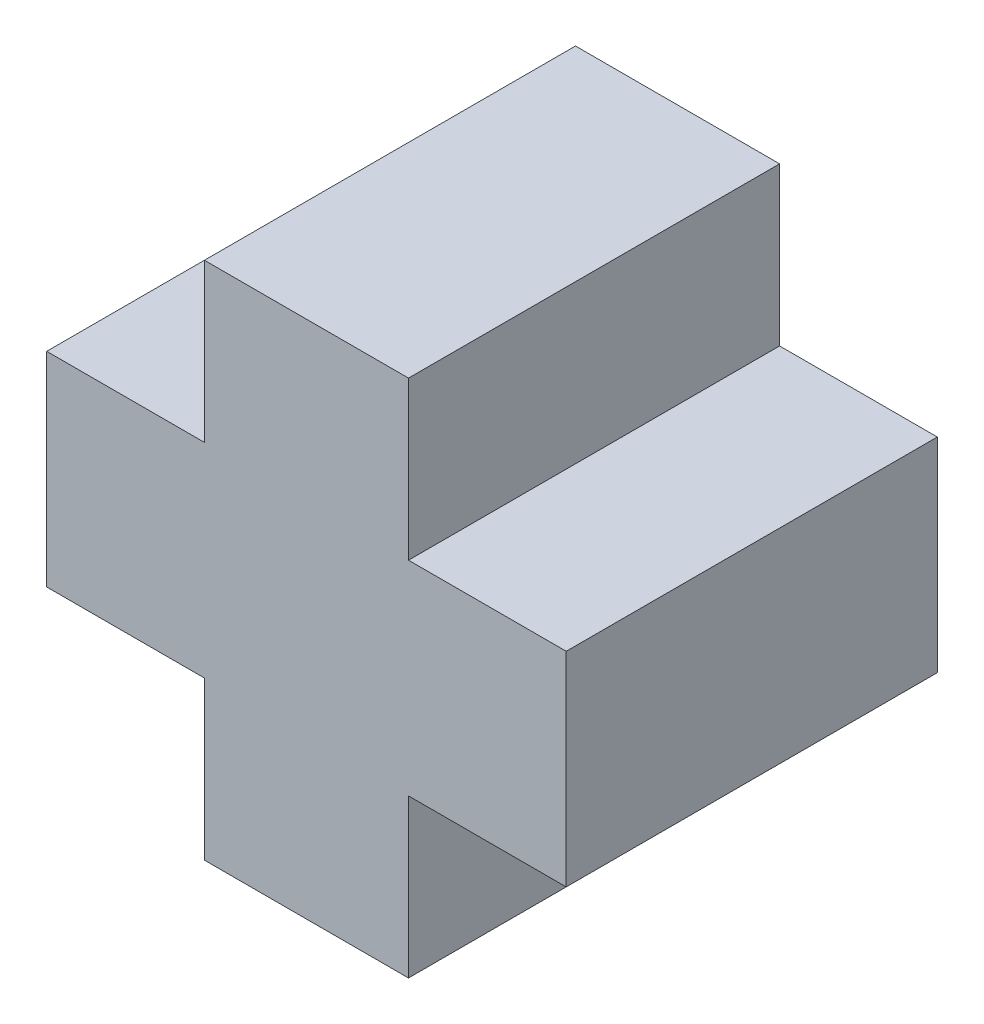
SolidWorks part; units mm, degrees
ref_plane "Front Plane" through (0, 0, 0) normal (0, 0, 1) x (1, 0, 0)
ref_plane "Top Plane" through (0, 0, 0) normal (0, 1, 0) x (1, 0, 0)
ref_plane "Right Plane" through (0, 0, 0) normal (1, 0, 0) x (0, 0, -1)
sketch "Sketch1" plane through (0, 0, 0) normal (0, 0, 1) x (1, 0, 0)
  line L0 (-2.75, 2.75) -> (-2.75, 7)
  line L1 (7, 2.75) -> (2.75, 2.75)
  line L2 (7, 2.75) -> (7, -2.75)
  line L3 (7, -2.75) -> (2.75, -2.75)
  line L4 (-7, 2.75) -> (-7, -2.75)
  line L5 (7, 2.75) -> (-7, -2.75) construction
  line L6 (7, -2.75) -> (-7, 2.75) construction
  line L7 (2.75, -7) -> (-2.75, -7)
  line L8 (2.75, -7) -> (2.75, -2.75)
  line L9 (2.75, 7) -> (-2.75, 7)
  line L10 (-2.75, -7) -> (-2.75, -2.75)
  line L11 (2.75, -7) -> (-2.75, 7) construction
  line L12 (2.75, 7) -> (-2.75, -7) construction
  line L13 (-2.75, 2.75) -> (-7, 2.75)
  line L14 (2.75, 2.75) -> (2.75, 7)
  line L15 (-2.75, -2.75) -> (-7, -2.75)
  point P0 (0, 0)
  point P5 (0, 0)
  dimension "D1" = 5.5
  dimension "D2" = 5.5
  dimension "D3" = 14
  dimension "D4" = 14
extrude "Boss-Extrude1" add sketch "Sketch1" along normal blind 10
